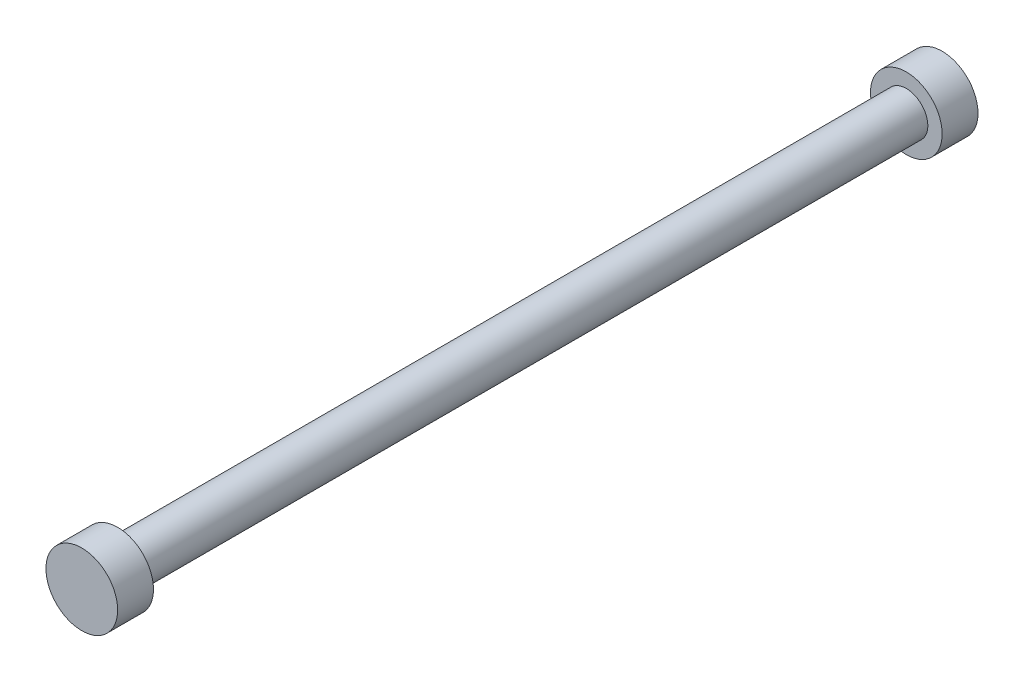
SolidWorks part; units mm, degrees
ref_plane "Front Plane" through (0, 0, 0) normal (0, 0, 1) x (1, 0, 0)
ref_plane "Top Plane" through (0, 0, 0) normal (0, 1, 0) x (1, 0, 0)
ref_plane "Right Plane" through (0, 0, 0) normal (1, 0, 0) x (0, 0, -1)
sketch "Sketch1" plane through (0, 0, 0) normal (0, 0, 1) x (1, 0, 0)
  circle A0 centre (0, 0) radius 3
  dimension "D1" = 6
extrude "Boss-Extrude1" add sketch "Sketch1" along normal mid plane 115
sketch "Sketch2" plane through (0, 0, 57.5) normal (0, 0, 1) x (1, 0, 0)
  circle A0 centre (0, 0) radius 5
  dimension "D1" = 10
extrude "Boss-Extrude2" add sketch "Sketch2" along normal mid plane 5
mirror "Mirror1" about plane through (0, 0, 0) normal (0, 0, 1) of "Boss-Extrude2"
